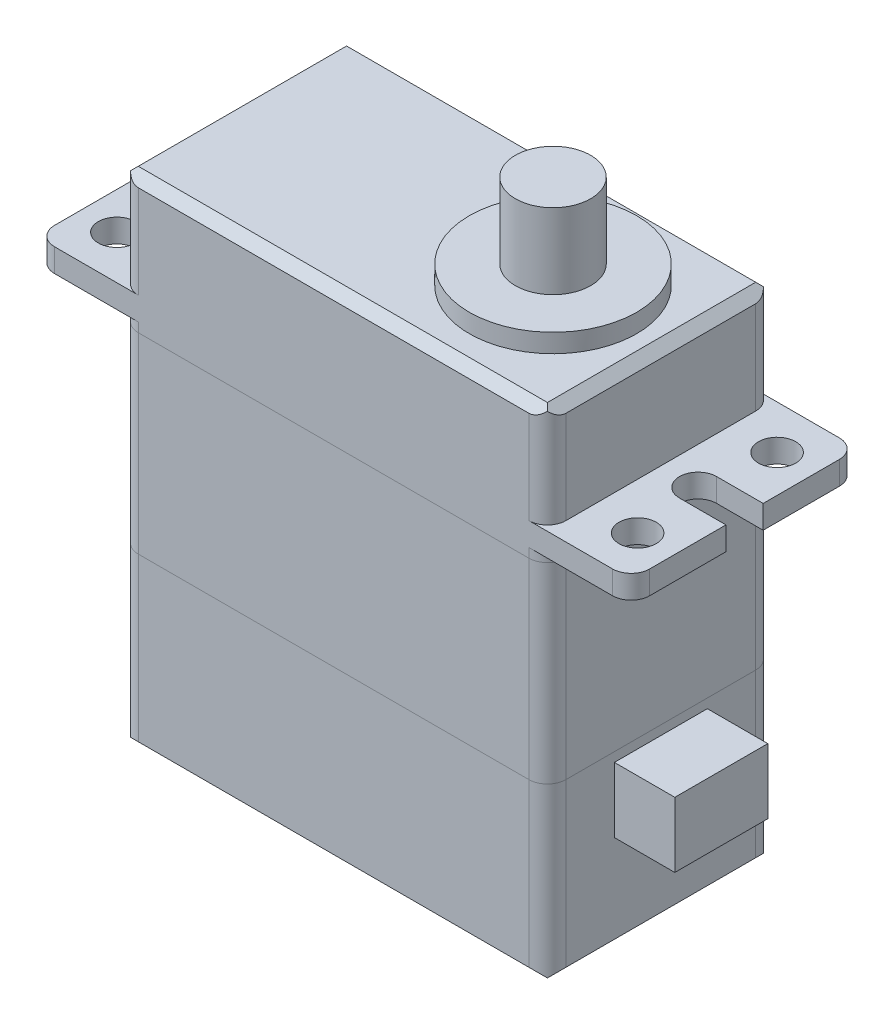
SolidWorks part; units mm, degrees
ref_plane "Plan de face" through (0, 0, 0) normal (0, 0, 1) x (1, 0, 0)
ref_plane "Plan de dessus" through (0, 0, 0) normal (0, 1, 0) x (1, 0, 0)
ref_plane "Plan de droite" through (0, 0, 0) normal (1, 0, 0) x (0, 0, -1)
sketch "Esquisse1" plane through (0, 0, 0) normal (0, 0, 1) x (1, 0, 0)
  line L1 (0, 0) -> (23, 0)
  line L2 (0, 0) -> (0, 26.8)
  line L3 (0, 26.8) -> (23, 26.8)
  line L4 (23, 0) -> (23, 26.8)
  dimension "D1" = 26.8
  dimension "D2" = 23
extrude "Boss.-Extru.1" add sketch "Esquisse1" along normal blind 12.2
sketch "Esquisse2" plane through (0, 0, 12.2) normal (0, 0, 1) x (1, 0, 0)
  line L1 (-4.5, 21.3) -> (27.5, 21.3)
  line L2 (-4.5, 21.3) -> (-4.5, 20.05)
  line L3 (-4.5, 20.05) -> (27.5, 20.05)
  line L4 (27.5, 21.3) -> (27.5, 20.05)
  line L5 (11.5, 26.8) -> (11.5, 21.3) construction
  line L6 (23, 26.8) -> (0, 26.8) construction
  line L7 (23, 26.8) -> (0, 26.8) construction
  dimension "D1" = 1.25
  dimension "D2" = 32
  dimension "D3" = 5.5
extrude "Boss.-Extru.2" add sketch "Esquisse2" against normal up to surface (12.2 mm away) up to face at (11.5, 13.4, 0)
sketch "Esquisse3" plane through (0, 26.8, 0) normal (0, 1, 0) x (1, 0, 0)
  line L0 (23, -12.2) -> (23, 0) construction
  line L1 (17.2, -6.1) -> (23, -6.1) construction
  circle A0 centre (17.2, -6.1) radius 4.5
  point P2 (12.7, -6.1)
  dimension "D2" = 9
  dimension "D1" = 10.3
extrude "Boss.-Extru.3" add sketch "Esquisse3" along normal blind 1
sketch "Esquisse4" plane through (0, 27.8, 0) normal (0, 1, 0) x (1, 0, 0)
  circle A0 centre (17.2, -6.1) radius 2.025
  dimension "D1" = 4.05
extrude "Boss.-Extru.4" add sketch "Esquisse4" along normal blind 4.05
sketch "Esquisse5" plane through (23, 0, 0) normal (1, 0, 0) x (0, 0, -1)
  line L0 (-12.2, 0) -> (0, 0) construction
  line L1 (-8.6, 8.74) -> (-3.6, 8.74)
  line L2 (-8.6, 8.74) -> (-8.6, 5.24)
  line L3 (-8.6, 5.24) -> (-3.6, 5.24)
  line L4 (-3.6, 8.74) -> (-3.6, 5.24)
  line L5 (-6.1, 5.24) -> (-6.1, 0) construction
  dimension "D1" = 5
  dimension "D2" = 8.74
  dimension "D3" = 3.5
extrude "Boss.-Extru.5" add sketch "Esquisse5" along normal blind 3.25
sketch "Esquisse6" plane through (0, 0, 0) normal (0, 0, -1) x (-1, 0, 0)
  line L0 (-23, 19.55) -> (0, 19.55)
  line L1 (-23, 0) -> (-23, 20.05) construction
  line L2 (0, 20.05) -> (0, 0) construction
  line L3 (-23, 9.24) -> (0, 9.24)
  line L4 (-23, 20.05) -> (-27.5, 20.05) construction
  line L5 (-26.25, 8.74) -> (-23, 8.74) construction
  point P10 (-24.625, 8.74)
  dimension "D1" = 0.5
  dimension "D2" = 0.5
split line "Ligne de séparation1"
sketch "Esquisse7" plane through (0, 21.3, 0) normal (0, 1, 0) x (1, 0, 0)
  line L0 (30, -6.1) -> (25, -6.1) construction
  line L1 (27.5, 0) -> (27.5, -12.2) construction
  line L2 (30, -7.1) -> (25, -7.1)
  line L3 (30, -5.1) -> (25, -5.1)
  line L4 (25.5, -2.35) -> (25.5, -9.85) construction
  line L5 (25.5, -6.1) -> (27.5, -6.1) construction
  line L6 (0, 0) -> (23, 0) construction
  line L7 (23, -12.2) -> (23, 0) construction
  line L8 (11.5, 0) -> (11.5, -12.2) construction
  line L9 (23, 0) -> (0, 0) construction
  line L10 (23, -12.2) -> (0, -12.2) construction
  line L11 (-2.5, -6.1) -> (-4.5, -6.1) construction
  line L12 (-2.5, -2.35) -> (-2.5, -9.85) construction
  line L13 (-7, -6.1) -> (-2, -6.1) construction
  line L14 (-7, -5.1) -> (-2, -5.1)
  line L15 (-7, -7.1) -> (-2, -7.1)
  line L16 (0, -12.2) -> (0, 0) construction
  circle A0 centre (25.5, -2.35) radius 1
  circle A1 centre (25.5, -9.85) radius 1
  arc A2 (30, -7.1) -> (30, -5.1) centre (30, -6.1) ccw
  arc A3 (25, -5.1) -> (25, -7.1) centre (25, -6.1) ccw
  circle A4 centre (-2.5, -9.85) radius 1
  circle A5 centre (-2.5, -2.35) radius 1
  arc A6 (-7, -5.1) -> (-7, -7.1) centre (-7, -6.1) ccw
  arc A7 (-2, -7.1) -> (-2, -5.1) centre (-2, -6.1) ccw
  point P8 (27.5, -6.1)
  point P15 (11.5, 0)
  point P34 (-4.5, -6.1)
  dimension "D1" = 2
  dimension "D2" = 1
  dimension "D7" = 1
  dimension "D3" = 7.5
  dimension "D4" = 14
  dimension "D5" = 2
  dimension "D6" = 2
extrude "Enlèv. mat.-Extru.1" cut sketch "Esquisse7" against normal up to surface (1.25 mm away) up to face at (-2.25, 20.05, 6.1)
chamfer "Chanfrein1" distance 0.5 angle 45 8 edges at (11.5, 0, 12.2) (23, 0, 6.1) (11.5, 0, 0) (0, 0, 6.1) (11.5, 26.8, 12.2) (23, 26.8, 6.1) (11.5, 26.8, 0) (0, 26.8, 6.1)
fillet "Congé1" radius 1 16 edges at (23, 4.87, 12.2) (23, 19.8, 12.2) (23, 14.395, 12.2) (23, 4.87, 0) (23, 19.8, 0) (23, 14.395, 0) (0, 19.8, 12.2) (0, 14.395, 12.2) (0, 4.87, 12.2) (0, 19.8, 0) (0, 14.395, 0) (0, 4.87, 0) (0, 23.8, 12.2) (23, 23.8, 12.2) (23, 23.8, 0) (0, 23.8, 0)
fillet "Congé2" radius 1 4 edges at (27.5, 20.675, 12.2) (-4.5, 20.675, 12.2) (27.5, 20.675, 0) (-4.5, 20.675, 0)
